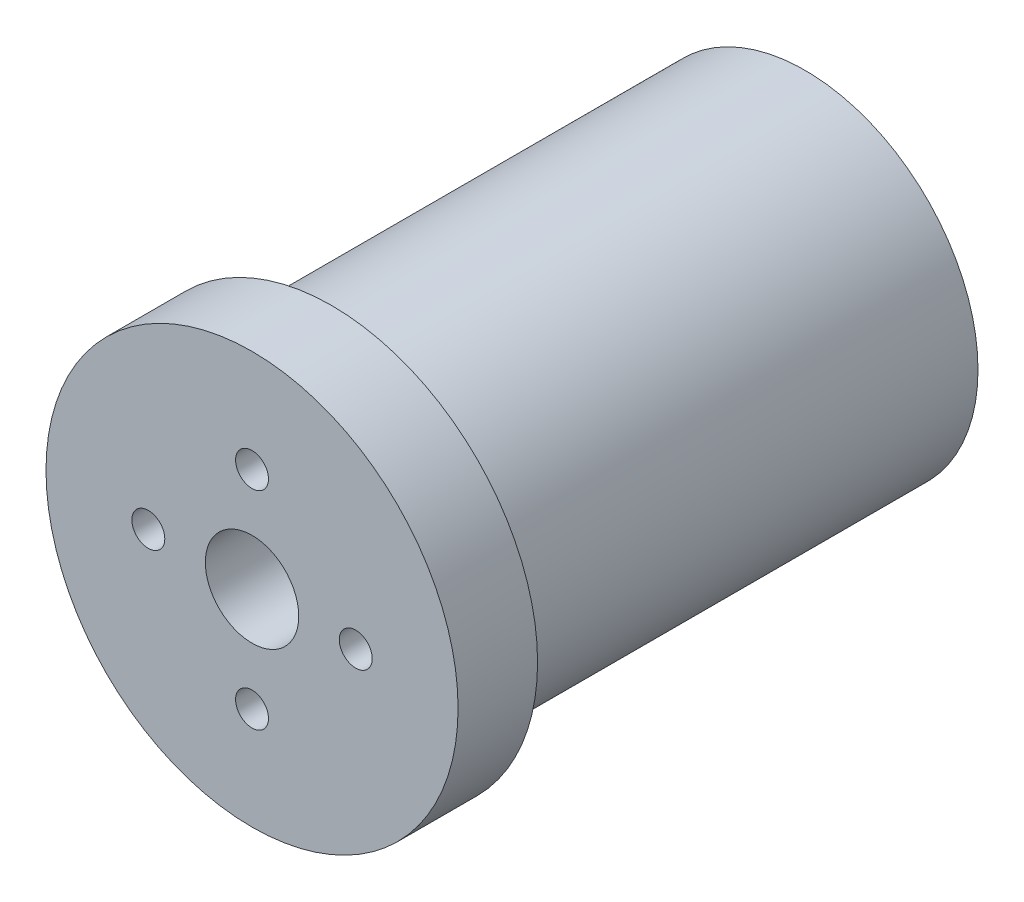
SolidWorks part; units mm, degrees
material "AISI 316 Annealed Stainless Steel Bar (SS)"
ref_plane "Front Plane" through (0, 0, 0) normal (1, 0, 0) x (0, 1, 0)
ref_plane "Top Plane" through (0, 0, 0) normal (0, 0, 1) x (0, 1, 0)
ref_plane "Right Plane" through (0, 0, 0) normal (0, 1, 0) x (-1, 0, 0)
sketch "Sketch1" plane through (0, 0, 0) normal (0, 0, 1) x (0, 1, 0)
  line L0 (0, 7.5) -> (0, -7.5) construction
  line L1 (-7.5, 0) -> (7.5, 0) construction
  circle A0 centre (0, 0) radius 12.5
  circle A1 centre (0, 0) radius 3.3782
  circle A2 centre (0, 7.5) radius 1.1906
  circle A3 centre (-7.5, 0) radius 1.1906
  circle A4 centre (7.5, 0) radius 1.1906
  circle A5 centre (0, -7.5) radius 1.1906
  dimension "D1" = 25
  dimension "D2" = 6.7564
  dimension "D3" = 2.3812
  dimension "D4" = 15
extrude "Boss-Extrude1" add sketch "Sketch1" along normal blind 40 contours A0 A5 A4 A3 A2 A1
sketch "Sketch2" plane through (0, 0, 0) normal (1, 0, 0) x (0, 1, 0)
  line L0 (-12.5, 0) -> (12.5, 0) construction
  line L1 (-12.5, 32) -> (-5, 32)
  line L2 (-12.5, 40) -> (-14.9, 40)
  line L3 (-12.5, 40) -> (-12.5, 34.25)
  line L4 (-12.5, 34.25) -> (-14.9, 34.25)
  line L5 (-14.9, 40) -> (-14.9, 34.25)
  line L6 (-12.5, 32) -> (-12.5, 8)
  line L7 (-12.5, 8) -> (-5, 8)
  line L8 (-5, 32) -> (-5, 8)
  line L9 (-6.3094, 40) -> (-8.6906, 40) construction
  line L10 (0, 0) -> (0, 40) construction
  line L11 (1.1906, 40) -> (-1.1906, 40) construction
  dimension "D1" = 5
  dimension "D2" = 8
  dimension "D3" = 8
  dimension "D4" = 14.9
  dimension "D5" = 5.75
revolve "Revolve1" add sketch "Sketch2" angle 360 about L10
